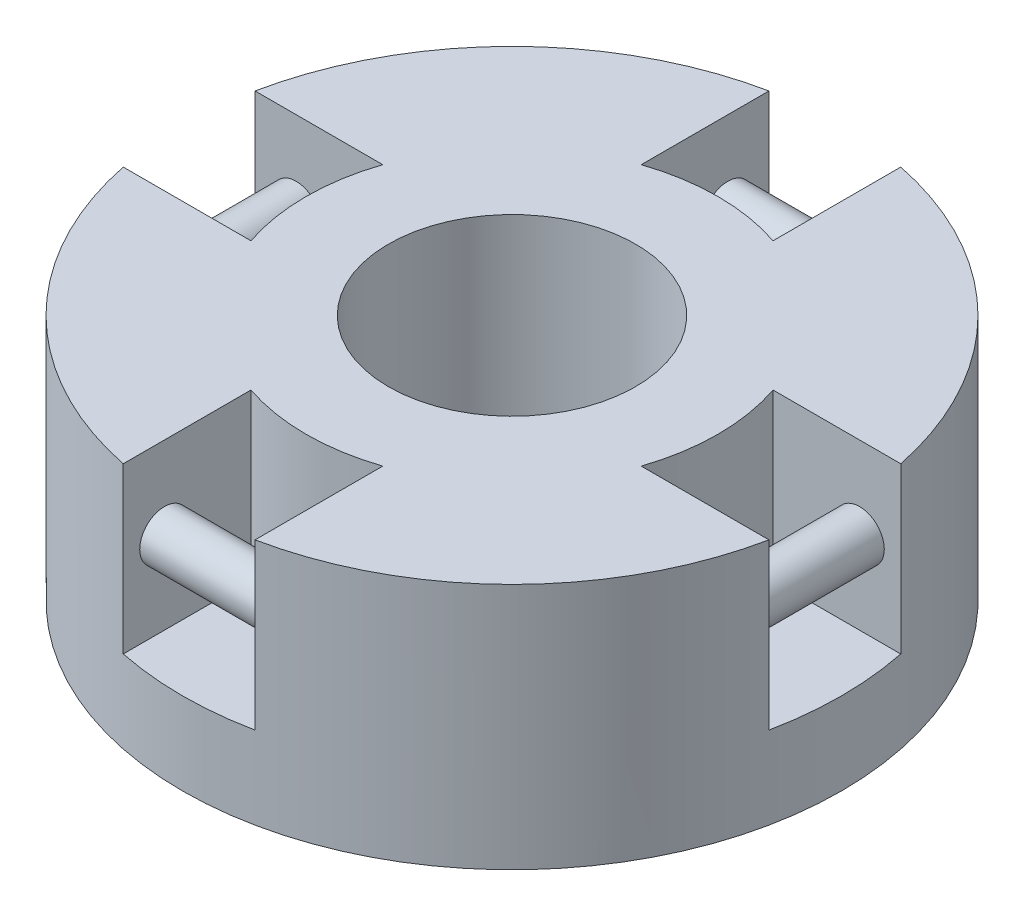
SolidWorks part; units mm, degrees
ref_plane "Front Plane" through (0, 0, 0) normal (0, 0, 1) x (1, 0, 0)
ref_plane "Top Plane" through (0, 0, 0) normal (0, 1, 0) x (1, 0, 0)
ref_plane "Right Plane" through (0, 0, 0) normal (1, 0, 0) x (0, 0, -1)
sketch "Sketch1" plane through (0, 0, 0) normal (0, 1, 0) x (1, 0, 0)
  circle A0 centre (0, 0) radius 20
  circle A1 centre (0, 0) radius 7.5
  dimension "D1" = 40
  dimension "D2" = 15
extrude "Boss-Extrude1" add sketch "Sketch1" along normal blind 15
sketch "Sketch2" plane through (0, 15, 0) normal (0, 1, 0) x (1, 0, 0)
  line L0 (-20, 0) -> (-12.5, 0) construction
  line L1 (-19.5959, -4) -> (-11.8427, -4)
  line L2 (0, 20) -> (0, 12.5) construction
  line L3 (-4, 19.5959) -> (-4, 11.8427)
  line L4 (-19.5959, 4) -> (-11.8427, 4)
  line L5 (4, 19.5959) -> (4, 11.8427)
  line L6 (4, 24.8259) -> (4, -29.7012) construction
  line L7 (0, 24.8259) -> (0, -29.7012) construction
  line L8 (-4, 24.8259) -> (-4, -29.7012) construction
  line L9 (-25.1252, 4) -> (27.4418, 4) construction
  line L10 (-25.1252, 0) -> (27.4418, 0) construction
  line L11 (-25.1252, -4) -> (27.4418, -4) construction
  line L12 (11.8427, 4) -> (19.5959, 4)
  line L13 (12.5, 0) -> (20, 0) construction
  line L14 (11.8427, -4) -> (19.5959, -4)
  line L15 (4, -11.8427) -> (4, -19.5959)
  line L16 (0, -12.5) -> (0, -20) construction
  line L17 (-4, -11.8427) -> (-4, -19.5959)
  circle A2 centre (0, 0) radius 20 construction
  circle A3 centre (0, 0) radius 12.5
  arc A4 (-4, -11.8427) -> (4, -11.8427) centre (0, 0) ccw
  arc A5 (-4, -19.5959) -> (4, -19.5959) centre (0, 0) ccw
  arc A6 (4, 11.8427) -> (-4, 11.8427) centre (0, 0) ccw
  arc A7 (4, 19.5959) -> (-4, 19.5959) centre (0, 0) ccw
  arc A8 (-11.8427, 4) -> (-11.8427, -4) centre (0, 0) ccw
  arc A9 (-19.5959, 4) -> (-19.5959, -4) centre (0, 0) ccw
  arc A10 (11.8427, -4) -> (11.8427, 4) centre (0, 0) ccw
  arc A11 (19.5959, -4) -> (19.5959, 4) centre (0, 0) ccw
  dimension "D1" = 4
  dimension "D2" = 4
  dimension "D3" = 5
extrude "Cut-Extrude1" cut sketch "Sketch2" against normal blind 10
sketch "Sketch4" plane through (0, 0, 4) normal (0, 0, -1) x (-1, 0, 0)
  line L0 (-19.5959, 5) -> (-19.5959, 15) construction
  line L1 (-4, 15) -> (-19.5959, 15) construction
  circle A0 centre (-17.0959, 10) radius 1.5
  dimension "D2" = 5
  dimension "D3" = 3
  dimension "D1" = 2.5
extrude "Boss-Extrude2" add sketch "Sketch4" along normal blind 10
pattern_circular "CirPattern1" count 4 over 360 about axis through (0, 15, 0) along (0, -1, 0) of "Boss-Extrude2"
sketch "Sketch3" plane through (0, 0, 0) normal (0, 0, 1) x (1, 0, 0)
  line L0 (-19.5959, 5) -> (-19.5959, 15) construction
  line L1 (0, 22.9484) -> (0, -11.1825) construction
  line L2 (-4, 15) -> (-19.5959, 15) construction
  circle A0 centre (-17.0959, 10) radius 1.5
  dimension "D1" = 3
  dimension "D2" = 2.5
  dimension "D3" = 5
